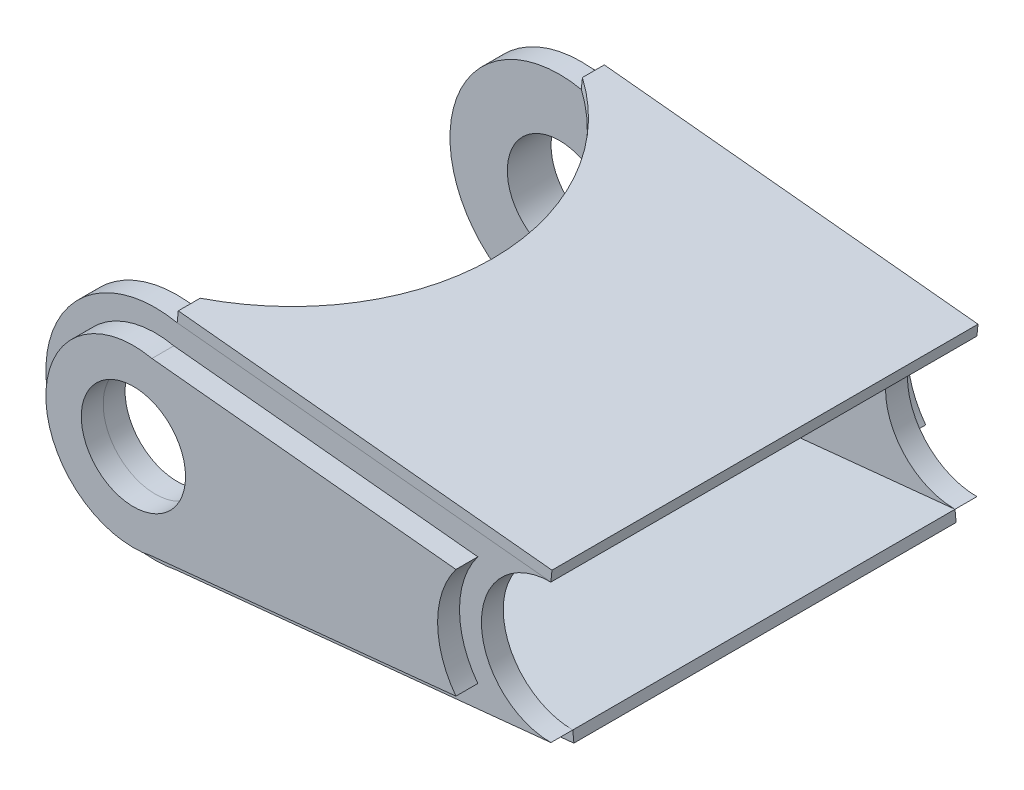
SolidWorks part; units mm, degrees
ref_plane "Front Plane" through (0, 0, 0) normal (0, 0, 1) x (1, 0, 0)
ref_plane "Top Plane" through (0, 0, 0) normal (0, 1, 0) x (1, 0, 0)
ref_plane "Right Plane" through (0, 0, 0) normal (1, 0, 0) x (0, 0, -1)
ref_plane "L" through (0, 0, 34.925) normal (0, 0, 1) x (1, 0, 0)
ref_plane "R" through (0, 0, -34.925) normal (0, 0, 1) x (1, 0, 0)
sketch "Sketch1" plane through (0, 0, 34.925) normal (0, 0, 1) x (1, 0, 0)
  line L0 (0, 12.7) -> (-68.2889, 19.5962)
  line L1 (-68.2889, -19.5962) -> (0, -12.7)
  arc A0 (0, 12.7) -> (0, -12.7) centre (0, 0) ccw
  arc A5 (-68.2889, 19.5962) -> (-68.2889, -19.5962) centre (-72.2876, 0) ccw
  dimension "D1" = 25.4
  dimension "D2" = 40
sketch "Sketch2" plane through (0, 0, -34.925) normal (0, 0, 1) x (1, 0, 0)
  line L0 (-68.2889, -19.5962) -> (0, -12.7) construction
  line L1 (0, 12.7) -> (-68.2889, 19.5962) construction
  line L2 (-68.2889, -19.5962) -> (0, -12.7)
  line L3 (0, 12.7) -> (-68.2889, 19.5962)
  arc A0 (-68.2889, 19.5962) -> (-68.2889, -19.5962) centre (-72.2876, 0) ccw construction
  arc A1 (0, 12.7) -> (0, -12.7) centre (0, 0) ccw construction
  arc A2 (-68.2889, 19.5962) -> (-68.2889, -19.5962) centre (-72.2876, 0) ccw
  arc A3 (0, 12.7) -> (0, -12.7) centre (0, 0) ccw
extrude "Boss-Extrude1" add sketch "Sketch1" along normal blind 4
extrude "Boss-Extrude2" add sketch "Sketch2" against normal blind 4
sketch "Sketch5" plane through (0, 0, 38.925) normal (0, 0, 1) x (1, 0, 0)
  line L4 (-13.3538, 10.0282) -> (-68.9025, 15.6378)
  line L5 (-68.9025, -15.6378) -> (-13.3538, -10.0282)
  line L6 (-13.3538, 10.0282) -> (-68.9025, 15.6378)
  line L7 (-68.9025, -15.6378) -> (-13.3538, -10.0282)
  arc A4 (-13.3538, 10.0282) -> (-13.3538, -10.0282) centre (0, 0) ccw
  arc A5 (-68.9025, 15.6378) -> (-68.9025, -15.6378) centre (-72.2876, 0) ccw
  arc A6 (-13.3538, 10.0282) -> (-13.3538, -10.0282) centre (0, 0) ccw
  arc A7 (-68.9025, 15.6378) -> (-68.9025, -15.6378) centre (-72.2876, 0) ccw
  dimension "D1" = 4
extrude "Boss-Extrude3" add sketch "Sketch5" along normal blind 4 separate body
sketch "Sketch6" plane through (0, 0, 42.925) normal (0, 0, 1) x (1, 0, 0)
  circle A1 centre (-72.2876, 0) radius 9.525
  dimension "D1" = 19.05
extrude "Cut-Extrude1" cut sketch "Sketch6" against normal up to surface (8 mm away)
mirror "Mirror1" about plane through (0, 0, 0) normal (0, 0, 1) of "Cut-Extrude1", "Boss-Extrude3"
ref_plane "Plane3" through (1.2696, 12.5718, 0) normal (0.1005, 0.9949, 0) x (0.9949, -0.1005, 0)
sketch "Sketch7" plane through (1.2696, 12.5718, 0) normal (0.1005, 0.9949, 0) x (0.9949, -0.1005, 0)
  line L4 (-1.276, -38.925) -> (-1.276, 38.925)
  line L5 (-69.9123, 38.925) -> (-1.276, 38.925)
  line L6 (-69.9123, 38.925) -> (-69.9123, 34.925)
  line L10 (-69.9123, -34.925) -> (-69.9123, -38.925)
  line L11 (-69.9123, -38.925) -> (-1.276, -38.925)
  arc A0 (-69.9123, 34.925) -> (-69.9123, -34.925) centre (-93.2413, 0) cw
  point P3 (-1.276, 34.925)
  point P12 (-1.276, -39.0374)
  point P14 (0, 0)
  dimension "D1" = 42
  dimension "D2" = 38.925
extrude "Boss-Extrude4" add sketch "Sketch7" along normal blind 2 separate body
ref_plane "Plane4" through (1.2696, -12.5718, 0) normal (0.1005, -0.9949, 0) x (-0.9949, -0.1005, 0)
sketch "Sketch8" plane through (1.2696, -12.5718, 0) normal (0.1005, -0.9949, 0) x (-0.9949, -0.1005, 0)
  line L1 (69.9123, 34.925) -> (1.276, 34.925)
  line L3 (69.9123, -34.925) -> (1.276, -34.925)
  line L4 (1.276, 34.925) -> (1.276, -34.925)
  arc A0 (69.9123, -34.925) -> (69.9123, 34.925) centre (93.2413, 0) cw
  dimension "D1" = 42
extrude "Boss-Extrude5" add sketch "Sketch8" along normal blind 2 separate body
